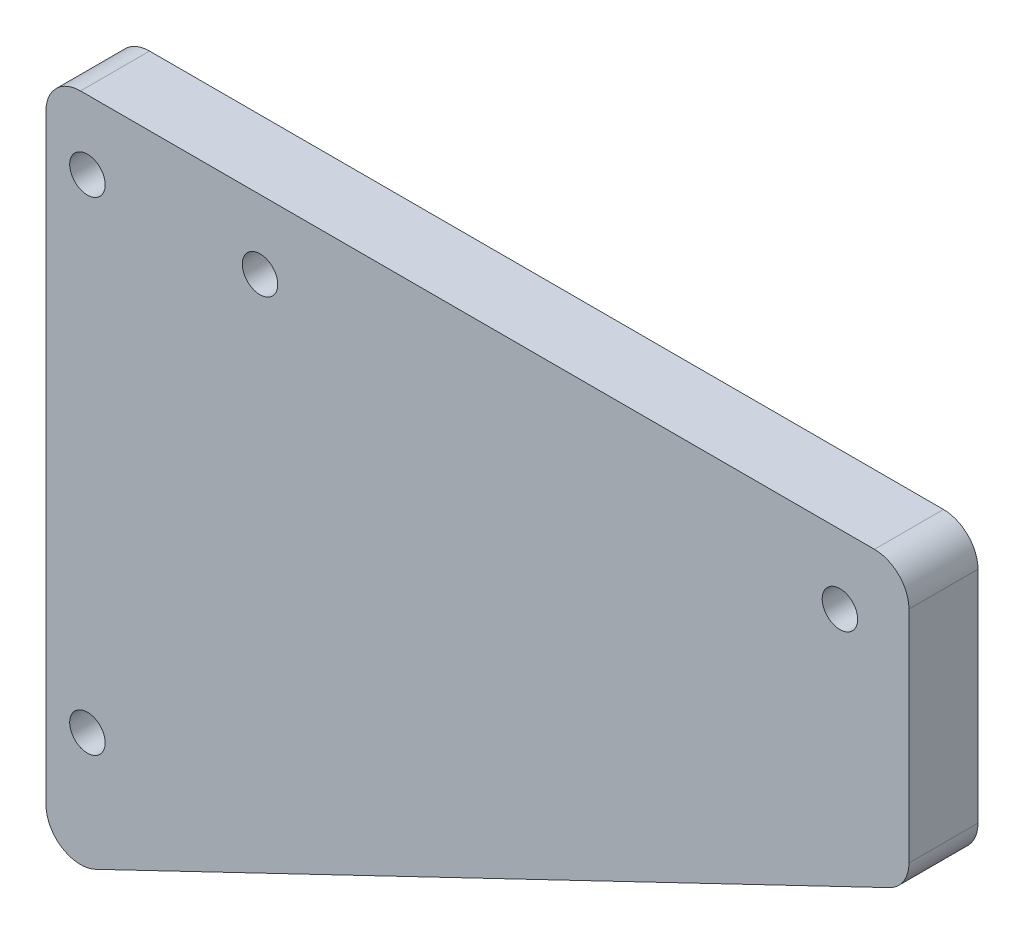
SolidWorks part; units mm, degrees
material "Acrylic (Medium-high impact)"
ref_plane "Front Plane" through (0, 0, 0) normal (0, 0, 1) x (1, 0, 0)
ref_plane "Top Plane" through (0, 0, 0) normal (0, 1, 0) x (1, 0, 0)
ref_plane "Right Plane" through (0, 0, 0) normal (1, 0, 0) x (0, 0, -1)
sketch "Sketch1" plane through (0, 0, 0) normal (0, 0, 1) x (1, 0, 0)
  line L1 (-38.1, -57.15) -> (41.275, -19.05)
  line L2 (-38.1, -57.15) -> (-38.1, 6.35)
  line L3 (-38.1, 6.35) -> (41.275, 6.35)
  line L4 (41.275, -19.05) -> (41.275, 6.35)
  point P0 (0, 0)
  dimension "D1" = 25.4
  dimension "D2" = 79.375
  dimension "D3" = 63.5
  dimension "D4" = 6.35
  dimension "D5" = 38.1
extrude "Boss-Extrude1" add sketch "Sketch1" along normal blind 6.35
sketch "Sketch2" plane through (0, 0, 6.35) normal (0, 0, 1) x (1, 0, 0)
  line L0 (-38.1, 0) -> (-34.29, 0) construction
  line L1 (-38.1, 6.35) -> (-38.1, -57.15) construction
  line L2 (-34.29, 0) -> (-18.415, 0) construction
  line L3 (-18.415, 0) -> (34.925, 0) construction
  line L5 (-34.29, 0) -> (-34.29, -44.45) construction
  line L6 (41.275, -19.05) -> (41.275, 6.35) construction
  dimension "D1" = 15.875
  dimension "D2" = 3.81
  dimension "D3" = 6.35
  dimension "D4" = 12.7
hole_wizard "#4 Clearance Hole1" positions "Sketch4" profile "Sketch3" hole size "#4" standard "Ansi Inch"
sketch "Sketch4" plane through (0, 0, 6.35) normal (0, 0, 1) x (1, 0, 0)
  point P1 (-34.29, 0)
  point P4 (-18.415, 0)
  point P7 (34.925, 0)
  point P12 (-34.29, -44.45)
sketch "Sketch3" plane through (-34.29, 0, 6.35) normal (1, 0, 0) x (0, -1, 0)
  line L0 (0, 0) -> (0, 13.6806)
  line L1 (0, 13.6806) -> (1.6319, 12.7)
  line L2 (1.6319, 12.7) -> (1.6319, 0)
  line L5 (1.6319, 0) -> (0, 0)
  line L10 (0, 13.6806) -> (-1.6319, 12.7) construction
  line L11 (0, -6.35) -> (0, 107.95) construction
  dimension "Hole Dia." = 3.2639
  dimension "Hole Depth" = 12.7
  dimension "Drill Angle" = 118
fillet "Fillet1" radius 3.175 4 edges at (-38.1, -57.15, 3.175) (-38.1, 6.35, 3.175) (41.275, -19.05, 3.175) (41.275, 6.35, 3.175)
